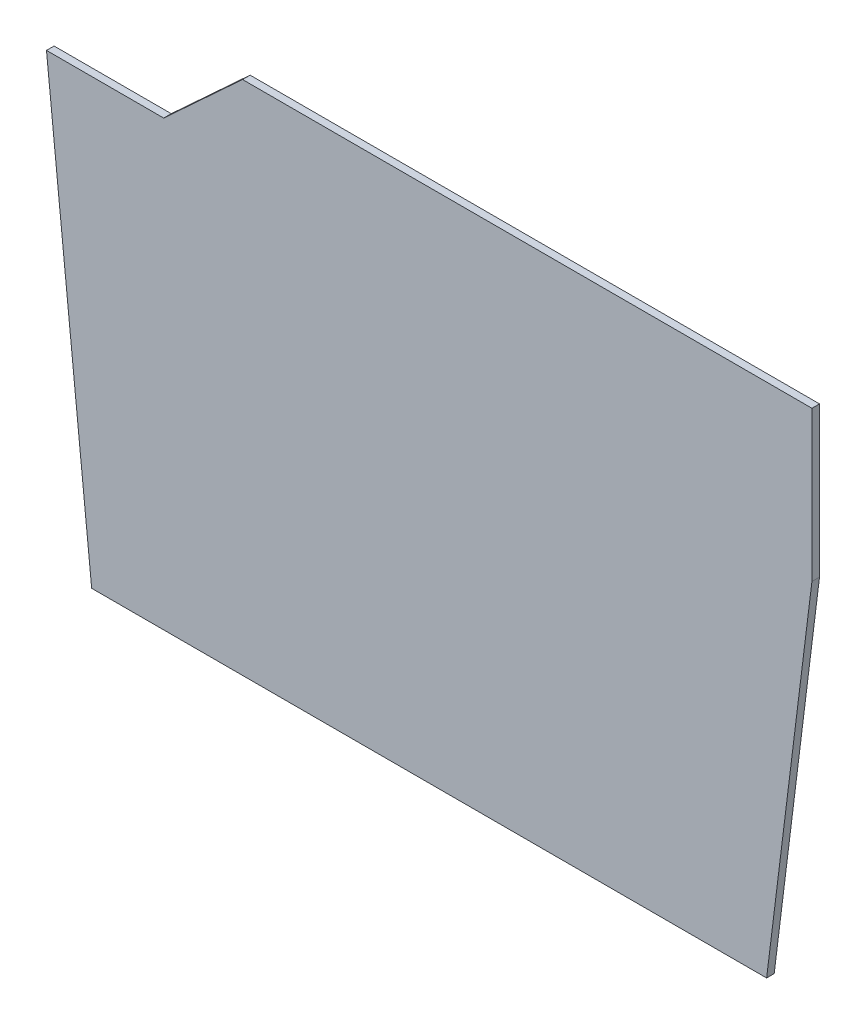
SolidWorks part; units mm, degrees
ref_plane "Plan de face" through (0, 0, 0) normal (0, 0, 1) x (1, 0, 0)
ref_plane "Plan de dessus" through (0, 0, 0) normal (0, 1, 0) x (1, 0, 0)
ref_plane "Plan de droite" through (0, 0, 0) normal (1, 0, 0) x (0, 0, -1)
sketch "Esquisse1" plane through (0, 0, 0) normal (0, 0, 1) x (1, 0, 0)
  line L0 (505.8433, -126) -> (505.8433, -26) construction
  line L1 (475.8433, -368.3) -> (505.8433, -126) construction
  line L2 (29, -368.3) -> (475.8433, -368.3) construction
  line L3 (505.8433, -26) -> (129, -26) construction
  line L4 (77, -74) -> (129, -26) construction
  line L5 (-1, -74) -> (77, -74) construction
  line L6 (-1, -74) -> (29, -368.3) construction
  line L7 (505.8433, -126) -> (505.8433, -26) construction
  line L8 (475.8433, -368.3) -> (505.8433, -126) construction
  line L9 (29, -368.3) -> (475.8433, -368.3) construction
  line L10 (505.8433, -26) -> (129, -26) construction
  line L11 (77, -74) -> (129, -26) construction
  line L12 (-1, -74) -> (77, -74) construction
  line L13 (-1, -74) -> (29, -368.3) construction
  line L21 (0.1071, -75) -> (29.9032, -367.3)
  line L22 (29.9032, -367.3) -> (474.9594, -367.3)
  line L23 (474.9594, -367.3) -> (504.8433, -125.9383)
  line L24 (504.8433, -125.9383) -> (504.8433, -27)
  line L25 (504.8433, -27) -> (129.391, -27)
  line L26 (77.391, -75) -> (129.391, -27)
  line L27 (0.1071, -75) -> (77.391, -75)
  dimension "D1" = 1
extrude "Boss.-Extru.1" add sketch "Esquisse1" along normal blind 5
